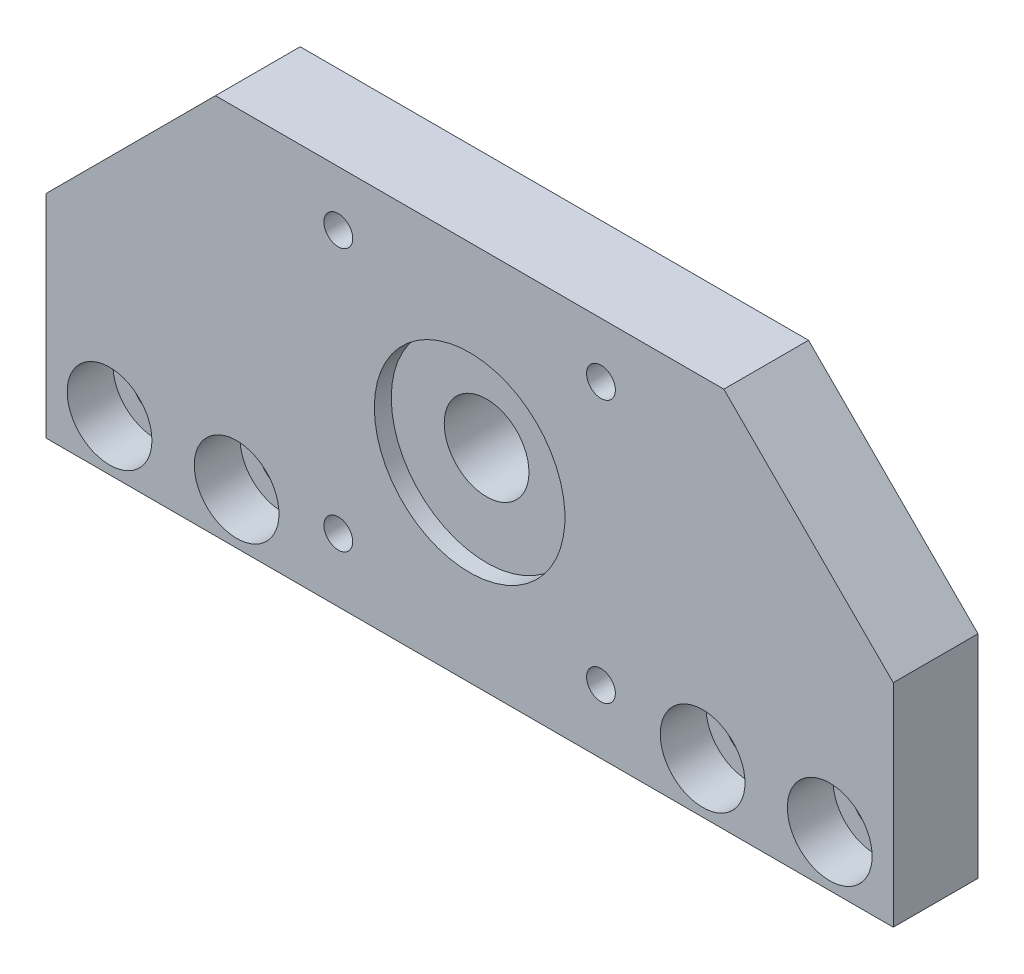
SolidWorks part; units mm, degrees
material "3.3535 (EN-AW 5754)"
ref_plane "Ön Düzlem" through (0, 0, 0) normal (0, 0, 1) x (1, 0, 0)
ref_plane "Üst Düzlem" through (0, 0, 0) normal (0, 1, 0) x (1, 0, 0)
ref_plane "Sağ Düzlem" through (0, 0, 0) normal (1, 0, 0) x (0, 0, -1)
sketch "Sketch1" plane through (0, 0, 0) normal (0, 0, 1) x (1, 0, 0)
  line L1 (50, -22.5) -> (-50, -22.5)
  line L2 (50, -22.5) -> (50, 22.5)
  line L3 (50, 22.5) -> (-50, 22.5)
  line L4 (-50, -22.5) -> (-50, 22.5)
  line L5 (50, -22.5) -> (-50, 22.5) construction
  line L6 (50, 22.5) -> (-50, -22.5) construction
  point P0 (0, 0)
  dimension "D1" = 45
  dimension "D2" = 100
extrude "Boss-Extrude1" add sketch "Sketch1" along normal mid plane 10
sketch "Sketch2" plane through (0, 0, 5) normal (0, 0, 1) x (1, 0, 0)
  line L0 (50, 22.5) -> (-50, 22.5) construction
  line L1 (15.5, -15) -> (-15.5, -15) construction
  line L2 (15.5, -15) -> (15.5, 16) construction
  line L3 (15.5, 16) -> (-15.5, 16) construction
  line L4 (-15.5, -15) -> (-15.5, 16) construction
  line L5 (15.5, -15) -> (-15.5, 16) construction
  line L6 (15.5, 16) -> (-15.5, -15) construction
  circle A0 centre (0, 0.5) radius 5
  circle A1 centre (-15.5, 16) radius 1.25
  circle A2 centre (15.5, 16) radius 1.25
  circle A3 centre (15.5, -15) radius 1.25
  circle A4 centre (-15.5, -15) radius 1.25
  point P2 (0, 0.5)
  point P8 (11.0821, 0)
  point P10 (0, 0)
  point P15 (0, 0)
  point P18 (0, 0)
  dimension "D1" = 10
  dimension "D4" = 2.5
  dimension "D2" = 31
  dimension "D3" = 31
  dimension "D5" = 22
  dimension "D6" = 22
chamfer "Chamfer1" distance 20 angle 45 2 edges at (50, 22.5, 0) (-50, 22.5, 0)
hole_wizard "CBORE for M5 Hex Socket Head Cap Screw2" positions "Sketch7" profile "Sketch4" counterbore size "M5" standard "ISO" end condition through all
sketch "Sketch7" plane through (0, 0, 5) normal (0, 0, 1) x (1, 0, 0)
  line L0 (-50, 2.5) -> (-50, -22.5) construction
  line L1 (-50, -16.5) -> (50, -16.5) construction
  line L2 (50, -22.5) -> (50, 2.5) construction
  line L4 (-50, -22.5) -> (50, -22.5) construction
  point P0 (-42.5, -16.5)
  point P5 (-27.5, -16.5)
  point P7 (27.5, -16.5)
  point P9 (42.5, -16.5)
  dimension "D1" = 7.5
  dimension "D2" = 15
  dimension "D4" = 6
  dimension "D5" = 7.5
  dimension "D6" = 15
sketch "Sketch4" plane through (-42.5, -16.5, 5) normal (1, 0, 0) x (0, -1, 0)
  line L0 (0, 0) -> (0, 10)
  line L1 (0, 10) -> (2.75, 10)
  line L3 (2.75, 10) -> (2.75, 5.4)
  line L4 (2.75, 5.4) -> (5, 5.4)
  line L5 (5, 5.4) -> (5, 0)
  line L7 (5, 0) -> (0, 0)
  line L11 (0, -6.35) -> (0, 107.95) construction
  dimension "Thru Hole Dia." = 5.5
  dimension "Thru Hole Depth" = 10
  dimension "C'Bore Dia." = 10
  dimension "C'Bore Depth" = 5.4
sketch "Sketch9" plane through (0, -22.5, 0) normal (0, -1, 0) x (1, 0, 0)
  line L0 (-50, -5) -> (50, -5) construction
  line L1 (-18, -5) -> (18, -5)
  line L2 (-18, -5) -> (-18, -1)
  line L3 (-18, -1) -> (18, -1)
  line L4 (18, -5) -> (18, -1)
  point P7 (0, -5)
  dimension "D1" = 4
  dimension "D2" = 36
extrude "Cut-Extrude2" [suppressed] cut sketch "Sketch9" against normal blind 10
hole_wizard "CBORE for M3 Hex Socket Head Cap Screw1" positions "Sketch10" profile "Sketch11" counterbore size "M3" standard "ISO" end condition through all
sketch "Sketch10" plane through (0, 0, -5) normal (0, 0, 1) x (1, 0, 0)
  point P0 (-15.5, 16)
  point P3 (15.5, 16)
  point P6 (15.5, -15)
  point P9 (-15.5, -15)
  point P15 (0, 0)
sketch "Sketch11" plane through (-15.5, 16, -5) normal (1, 0, 0) x (0, 1, 0)
  line L0 (0, 0) -> (0, 10)
  line L1 (0, 10) -> (1.7, 10)
  line L3 (1.7, 10) -> (1.7, 3.4)
  line L4 (1.7, 3.4) -> (3.25, 3.4)
  line L5 (3.25, 3.4) -> (3.25, 0)
  line L7 (3.25, 0) -> (0, 0)
  line L11 (0, -6.35) -> (0, 107.95) construction
  dimension "Thru Hole Dia." = 3.4
  dimension "Thru Hole Depth" = 10
  dimension "C'Bore Dia." = 6.5
  dimension "C'Bore Depth" = 3.4
extrude "Cut-Extrude3" cut sketch "Sketch2" against normal blind 10 contours A0
sketch "Sketch12" plane through (0, 0, 5) normal (0, 0, -1) x (-1, 0, 0)
  circle A0 centre (0, 0) radius 11.25
  dimension "D1" = 22.5
extrude "Cut-Extrude4" cut sketch "Sketch12" along normal blind 2
